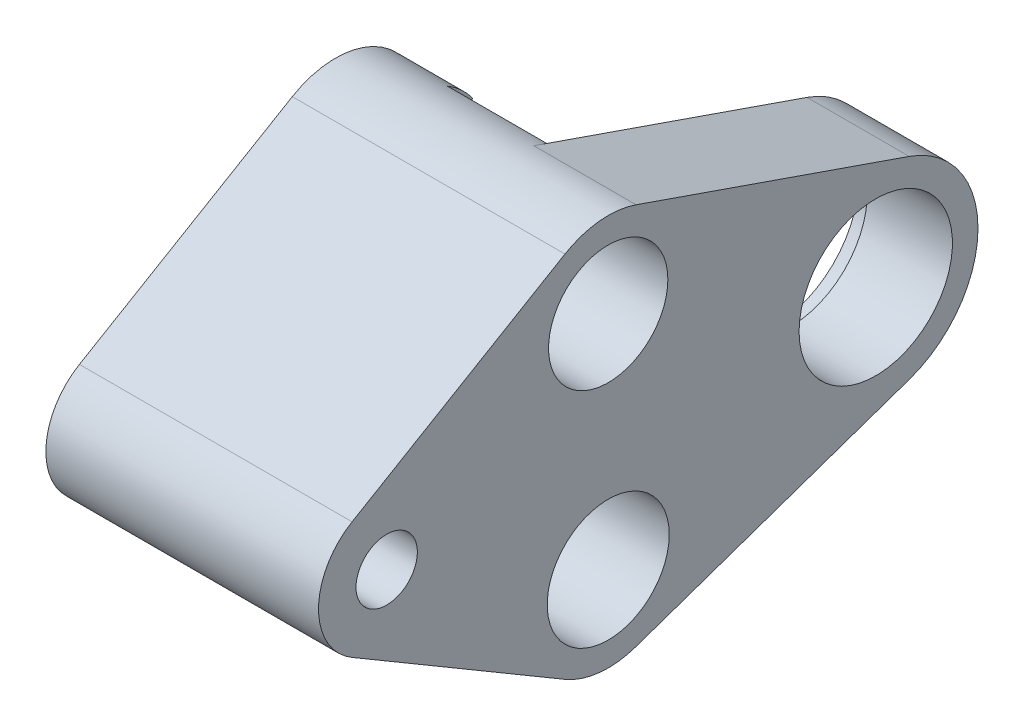
SolidWorks part; units mm, degrees
ref_plane "Front Plane" through (0, 0, 0) normal (0, 0, 1) x (1, 0, 0)
ref_plane "Top Plane" through (0, 0, 0) normal (0, 1, 0) x (1, 0, 0)
ref_plane "Right Plane" through (0, 0, 0) normal (1, 0, 0) x (0, 0, -1)
sketch "Sketch1" plane through (0, 0, 0) normal (1, 0, 0) x (0, 0, -1)
  line L0 (0, 16.51) -> (0, 0) construction
  line L1 (0, 8.255) -> (19.939, 8.255) construction
  line L3 (2.0795, 22.5098) -> (22.4345, 15.4548)
  line L4 (2.0795, -5.9998) -> (22.4345, 1.0552)
  line L5 (-19.0891, 12.6316) -> (-3.2238, 21.9808)
  line L6 (-19.0891, 3.8784) -> (-3.2238, -5.4708)
  circle A0 centre (19.939, 8.255) radius 5.715
  arc A1 (22.4345, 1.0552) -> (22.4345, 15.4548) centre (19.939, 8.255) ccw
  circle A2 centre (0, 16.51) radius 2.286
  circle A3 centre (0, 0) radius 2.286
  arc A4 (2.0795, 22.5098) -> (-3.2238, 21.9808) centre (0, 16.51) ccw
  arc A5 (-3.2238, -5.4708) -> (2.0795, -5.9998) centre (0, 0) ccw
  circle A6 centre (19.939, 8.255) radius 1.27 construction
  circle A7 centre (-16.51, 8.255) radius 2.286
  arc A8 (-19.0891, 12.6316) -> (-19.0891, 3.8784) centre (-16.51, 8.255) ccw
  dimension "D1" = 16.51
  dimension "D2" = 4.572
  dimension "D4" = 11.43
  dimension "D5" = 12.7
  dimension "D6" = 7.62
  dimension "D3" = 16.51
  dimension "D7" = 5.08
extrude "Boss-Extrude1" add sketch "Sketch1" along normal blind 7.62
sketch "Sketch2" plane through (0, 0, 0) normal (-1, 0, 0) x (0, 0, 1)
  line L0 (0, 16.51) -> (0, 0) construction
  line L4 (3.2238, 21.9808) -> (19.0891, 12.6316) construction
  line L5 (3.2238, 21.9808) -> (19.0891, 12.6316)
  line L6 (3.2238, -5.4708) -> (19.0891, 3.8784)
  arc A0 (3.2238, 21.9808) -> (-5.1355, 20.2449) centre (0, 16.51) ccw
  arc A1 (-5.1355, -3.7349) -> (3.2238, -5.4708) centre (0, 0) ccw
  circle A2 centre (0, 16.51) radius 2.286
  circle A3 centre (0, 0) radius 2.286
  circle A4 centre (0, 0) radius 2.286 construction
  arc A5 (-5.1355, -3.7349) -> (-5.1355, 20.2449) centre (-19.939, 8.255) ccw
  arc A6 (3.2238, 21.9808) -> (-2.0795, 22.5098) centre (0, 16.51) ccw construction
  circle A7 centre (16.51, 8.255) radius 2.286
  arc A8 (19.0891, 3.8784) -> (19.0891, 12.6316) centre (16.51, 8.255) ccw
  point P4 (20.32, 0)
  arc M2 (-2.0795, -5.9998) -> (3.2238, -5.4708) centre (0, 0) ccw
  arc M4 (3.2238, 21.9808) -> (-2.0795, 22.5098) centre (0, 16.51) ccw
  arc M17 (19.0891, 3.8784) -> (19.0891, 12.6316) centre (16.51, 8.255) ccw
  line M18 (19.0891, 12.6316) -> (3.2238, 21.9808)
  line M19 (3.2238, -5.4708) -> (19.0891, 3.8784)
  circle M20 centre (16.51, 8.255) radius 2.286
  dimension "D1" = 38.1
extrude "Boss-Extrude2" add sketch "Sketch2" along normal blind 12.7 contours A5 A2 A3 A1 A0 M2 M19 M17 M18 M4 M20
sketch "Sketch3" plane through (0, 0, 0) normal (-1, 0, 0) x (0, 0, 1)
  circle A0 centre (-19.939, 8.255) radius 6.35
  circle A1 centre (-19.939, 8.255) radius 5.715 construction
  dimension "D1" = 12.7
extrude "Cut-Extrude1" cut sketch "Sketch3" against normal blind 1.27
sketch "Sketch5" plane through (0, 0, 0) normal (-1, 0, 0) x (0, 0, 1)
  circle A0 centre (-19.939, 8.255) radius 21.59
  dimension "D1" = 43.18
extrude "Cut-Extrude3" cut sketch "Sketch5" along normal blind 7.62
sketch "Sketch4" plane through (7.62, 0, 0) normal (1, 0, 0) x (0, 0, -1)
  circle A0 centre (0, 0) radius 4.5466
  circle A1 centre (0, 16.51) radius 4.445
  dimension "D1" = 9.0932
  dimension "D2" = 8.89
extrude "Cut-Extrude2" cut sketch "Sketch4" against normal up to surface (15.24 mm away)
